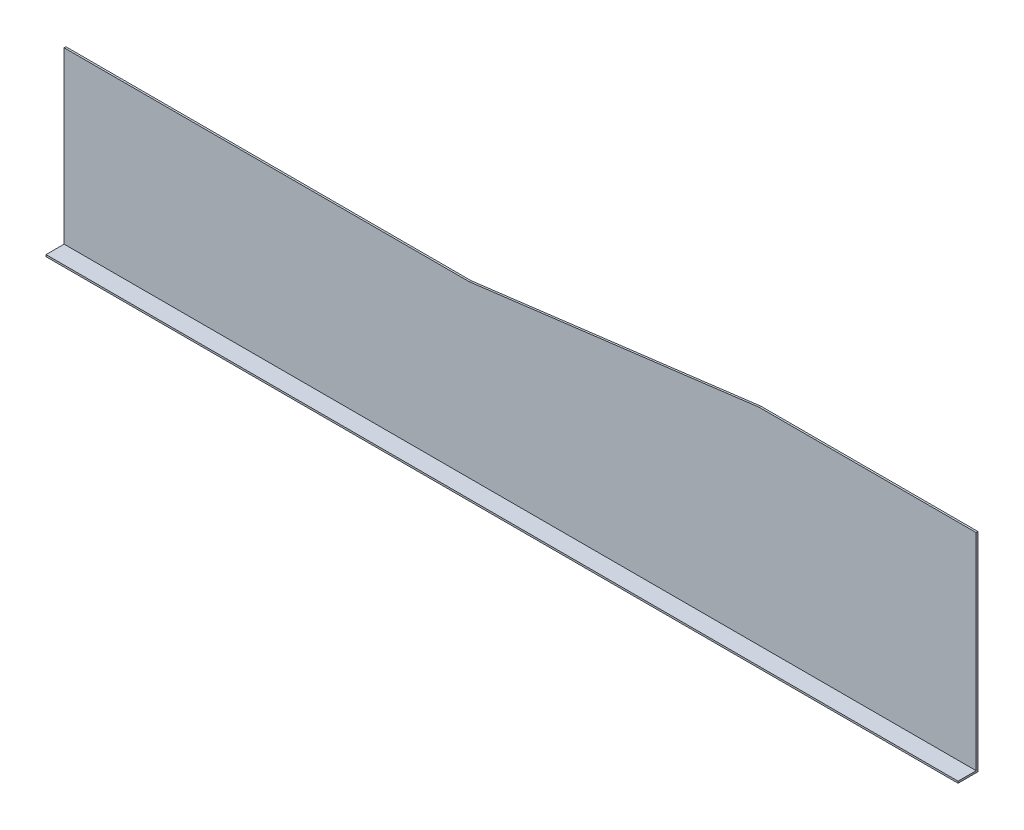
SolidWorks part; units mm, degrees
ref_plane "Front Plane" through (0, 0, 0) normal (0, 0, 1) x (1, 0, 0)
ref_plane "Top Plane" through (0, 0, 0) normal (0, 1, 0) x (1, 0, 0)
ref_plane "Right Plane" through (0, 0, 0) normal (1, 0, 0) x (0, 0, -1)
sketch "Sketch1" plane through (0, 0, 0) normal (0, 0, 1) x (1, 0, 0)
  line L0 (0, 0) -> (0, 118.73)
  line L1 (0, 118.73) -> (280, 118.73)
  line L2 (280, 118.73) -> (480, 143.73)
  line L3 (480, 143.73) -> (630, 143.73)
  line L4 (630, 143.73) -> (630, 0)
  line L5 (630, 0) -> (0, 0)
  dimension "D1" = 143.73
  dimension "D2" = 118.73
  dimension "D3" = 630
  dimension "D4" = 280
  dimension "D5" = 200
extrude "Boss-Extrude1" add sketch "Sketch1" along normal blind 1.27
sketch "Sketch2" plane through (0, 0, 1.27) normal (0, 0, 1) x (1, 0, 0)
  line L0 (630, 0) -> (630, 143.73) construction
  line L1 (0, 0) -> (630, 0)
  line L2 (0, 0) -> (0, 1.27)
  line L3 (0, 1.27) -> (630, 1.27)
  line L4 (630, 0) -> (630, 1.27)
  dimension "D1" = 1.27
extrude "Boss-Extrude2" add sketch "Sketch2" along normal blind 12.5
